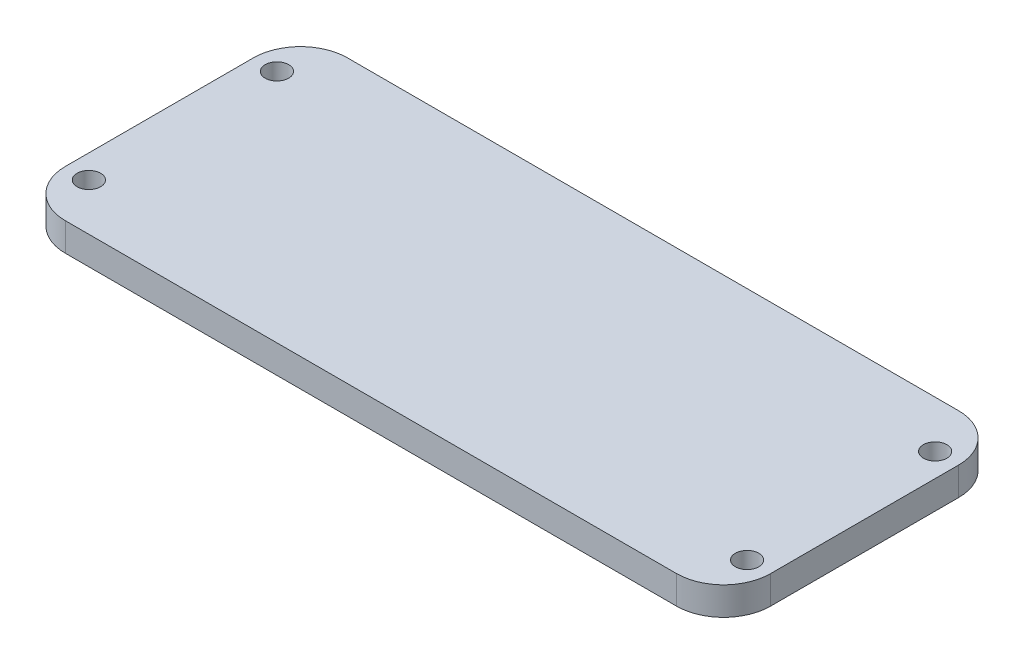
SolidWorks part; units mm, degrees
ref_plane "Alzado" through (0, 0, 0) normal (0, 0, 1) x (1, 0, 0)
ref_plane "Planta" through (0, 0, 0) normal (0, 1, 0) x (1, 0, 0)
ref_plane "Vista lateral" through (0, 0, 0) normal (1, 0, 0) x (0, 0, -1)
sketch "Croquis1" plane through (0, 0, 0) normal (0, 1, 0) x (1, 0, 0)
  line L0 (0, -25.6034) -> (0, 25.6034) construction
  line L2 (-32, -14.5) -> (-13, -14.5)
  line L3 (-37, -9.5) -> (-37, 9.5)
  line L4 (-32, 14.5) -> (-13, 14.5)
  line L5 (-8, -9.5) -> (-8, 9.5)
  line L6 (-37, -14.5) -> (-8, 14.5) construction
  line L7 (-37, 14.5) -> (-8, -14.5) construction
  line L8 (13, -14.5) -> (32, -14.5)
  line L9 (8, -9.5) -> (8, 9.5)
  line L10 (13, 14.5) -> (32, 14.5)
  line L11 (37, -9.5) -> (37, 9.5)
  line L12 (8, -14.5) -> (37, 14.5) construction
  line L13 (8, 14.5) -> (37, -14.5) construction
  arc A0 (8, 9.5) -> (13, 14.5) centre (13, 9.5) cw
  arc A1 (32, 14.5) -> (37, 9.5) centre (32, 9.5) cw
  arc A2 (32, -14.5) -> (37, -9.5) centre (32, -9.5) ccw
  arc A3 (13, -14.5) -> (8, -9.5) centre (13, -9.5) cw
  arc A4 (-32, -14.5) -> (-37, -9.5) centre (-32, -9.5) cw
  arc A5 (-13, -14.5) -> (-8, -9.5) centre (-13, -9.5) ccw
  arc A6 (-13, 14.5) -> (-8, 9.5) centre (-13, 9.5) cw
  arc A7 (-37, 9.5) -> (-32, 14.5) centre (-32, 9.5) cw
  point P0 (-22.5, 0)
  point P3 (0, 0)
  point P10 (22.5, 0)
  dimension "D7" = 5
  dimension "D1" = 29
  dimension "D2" = 29
  dimension "D3" = 29
  dimension "D4" = 8
  dimension "D5" = 8
  dimension "D6" = 29
extrude "Saliente-Extruir1" add sketch "Croquis1" along normal blind 2.8
sketch "Croquis2" plane through (0, 2.8, 0) normal (0, 1, 0) x (1, 0, 0)
  line L0 (-13, 14.5) -> (-32, 14.5) construction
  line L1 (-33, -12.5) -> (-12, -12.5)
  line L2 (-35, -10.5) -> (-35, 10.5)
  line L3 (-33, 12.5) -> (-12, 12.5)
  line L4 (-10, -10.5) -> (-10, 10.5)
  line L5 (-35, -12.5) -> (-10, 12.5) construction
  line L6 (-35, 12.5) -> (-10, -12.5) construction
  line L7 (12, -12.5) -> (33, -12.5)
  line L8 (10, -10.5) -> (10, 10.5)
  line L9 (12, 12.5) -> (33, 12.5)
  line L10 (35, -10.5) -> (35, 10.5)
  line L11 (10, -12.5) -> (35, 12.5) construction
  line L12 (10, 12.5) -> (35, -12.5) construction
  line L13 (32, 14.5) -> (13, 14.5) construction
  line L14 (8, 9.5) -> (8, -9.5) construction
  line L15 (-8, -9.5) -> (-8, 9.5) construction
  arc A0 (12, -12.5) -> (10, -10.5) centre (12, -10.5) cw
  arc A1 (33, -12.5) -> (35, -10.5) centre (33, -10.5) ccw
  arc A2 (33, 12.5) -> (35, 10.5) centre (33, 10.5) cw
  arc A3 (10, 10.5) -> (12, 12.5) centre (12, 10.5) cw
  arc A4 (-33, -12.5) -> (-35, -10.5) centre (-33, -10.5) cw
  arc A5 (-12, -12.5) -> (-10, -10.5) centre (-12, -10.5) ccw
  arc A6 (-12, 12.5) -> (-10, 10.5) centre (-12, 10.5) cw
  arc A7 (-35, 10.5) -> (-33, 12.5) centre (-33, 10.5) cw
  point P0 (-22.5, 0)
  point P5 (22.5, 0)
  point P15 (-22.5, 14.5)
  point P19 (22.5, 14.5)
  point P23 (8, 0)
  point P24 (-10, 0)
  point P27 (-8, 0)
  dimension "D5" = 2
  dimension "D1" = 25
  dimension "D2" = 25
  dimension "D3" = 25
  dimension "D4" = 25
extrude "Saliente-Extruir2" add sketch "Croquis2" along normal blind 3
ref_plane "Plano2" through (0, 6.5, 0) normal (0, 1, 0) x (1, 0, 0)
sketch "Croquis3" plane through (0, 6.5, 0) normal (0, 1, 0) x (1, 0, 0)
  line L0 (0, 0) -> (0, 29.1025) construction
  line L1 (65, -30) -> (-65, -30)
  line L2 (75, -20) -> (75, 20)
  line L3 (65, 30) -> (-65, 30)
  line L4 (-75, -20) -> (-75, 20)
  line L5 (75, -30) -> (-75, 30) construction
  line L6 (75, 30) -> (-75, -30) construction
  arc A0 (-65, -30) -> (-75, -20) centre (-65, -20) cw
  arc A1 (65, -30) -> (75, -20) centre (65, -20) ccw
  arc A2 (75, 20) -> (65, 30) centre (65, 20) ccw
  arc A3 (-65, 30) -> (-75, 20) centre (-65, 20) ccw
  circle A5 centre (-70, 20) radius 2.5
  circle A6 centre (-70, -20) radius 2.5
  circle A7 centre (70, -20) radius 2.5
  circle A8 centre (70, 20) radius 2.5
  point P0 (0, 0)
  dimension "D2" = 10
  dimension "D3" = 5
  dimension "D5" = 5
  dimension "D1" = 150
  dimension "60" = 60
  dimension "D4" = 5
  dimension "D6" = 5
  dimension "D7" = 40
  dimension "D8" = 10
extrude "Saliente-Extruir3" add sketch "Croquis3" along normal blind 6
